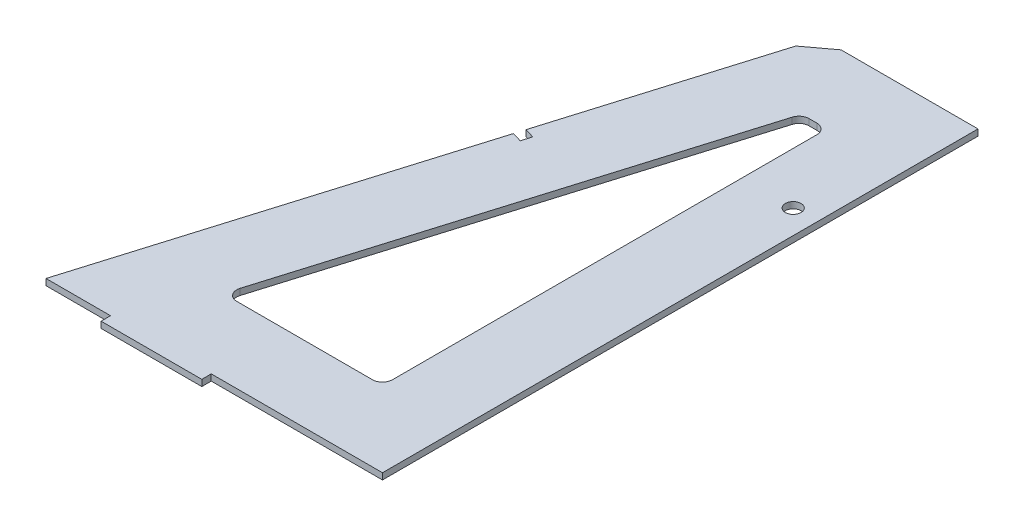
SolidWorks part; units mm, degrees
material "Balsa"
ref_plane "Front Plane" through (0, 0, 0) normal (0, 0, 1) x (1, 0, 0)
ref_plane "Top Plane" through (0, 0, 0) normal (0, 1, 0) x (1, 0, 0)
ref_plane "Right Plane" through (0, 0, 0) normal (1, 0, 0) x (0, 0, -1)
sketch "Sketch2" plane through (0, 0, 0) normal (0, 1, 0) x (1, 0, 0)
  line L0 (0, 0) -> (0, -214.2319) construction
  line L1 (0, 0) -> (202.3588, 0) construction
  line L2 (0, 0) -> (-115.8892, 0)
  line L3 (-115.8892, 0) -> (-25.4, 300.355)
  line L4 (-25.4, 300.355) -> (0, 300.355)
  line L5 (0, 300.355) -> (0, 0)
  dimension "D1" = 300.355
  dimension "D2" = 25.4
  dimension "D3" = 313.69
extrude "Boss-Extrude1" add sketch "Sketch2" along normal blind 3.175
sketch "Sketch4" plane through (0, 0, 0) normal (0, 0, 1) x (1, 0, 0)
  line L0 (-57.9446, 3.175) -> (-57.9446, 0) construction
  line L1 (-115.8892, 3.175) -> (0, 3.175) construction
  line L2 (-115.8892, 0) -> (0, 0) construction
  line L4 (-83.3446, 3.175) -> (-32.5446, 3.175)
  line L5 (-83.3446, 3.175) -> (-83.3446, 0)
  line L6 (-83.3446, 0) -> (-32.5446, 0)
  line L7 (-32.5446, 3.175) -> (-32.5446, 0)
  line L8 (-83.3446, 3.175) -> (-32.5446, 0) construction
  line L9 (-83.3446, 0) -> (-32.5446, 3.175) construction
  point P6 (-57.9446, 1.5875)
  dimension "D1" = 50.8
extrude "Boss-Extrude2" add sketch "Sketch4" along normal blind 4.7625
sketch "Sketch6" plane through (0, 0, 0) normal (1, 0, 0) x (0, 0, -1)
  line L4 (0, 0) -> (300.355, 0)
  line L5 (300.355, 0) -> (300.355, 3.175)
  line L6 (300.355, 3.175) -> (0, 3.175)
  line L7 (0, 3.175) -> (0, 0)
  line L8 (0, 0) -> (300.355, 0)
  line L9 (300.355, 0) -> (300.355, 3.175)
  line L10 (300.355, 3.175) -> (0, 3.175)
  line L11 (0, 3.175) -> (0, 0)
  dimension "D1" = 0
extrude "Boss-Extrude3" add sketch "Sketch6" along normal blind 53.819
sketch "Sketch7" plane through (0, 3.175, 0) normal (0, 1, 0) x (1, 0, 0)
  line L0 (41.754, 0) -> (41.754, 300.355) construction
  line L1 (-32.5446, 0) -> (53.819, 0) construction
  line L2 (53.819, 300.355) -> (-25.4, 300.355) construction
  line L3 (53.819, 300.355) -> (53.819, 0) construction
  line L4 (-28.3308, 290.6269) -> (-15.24, 300.355)
  line L5 (-25.4, 300.355) -> (-115.8892, 0) construction
  line L6 (-15.24, 300.355) -> (-25.4, 300.355)
  line L7 (-25.4, 300.355) -> (-28.3308, 290.6269)
  circle A0 centre (41.754, 219.202) radius 3.9687
  dimension "D2" = 7.9375
  dimension "D1" = 12.065
  dimension "D3" = 219.202
  dimension "D4" = 10.16
  dimension "D5" = 10.16
extrude "Cut-Extrude3" cut sketch "Sketch7" against normal through all
sketch "Sketch8" plane through (0, 3.175, 0) normal (0, 1, 0) x (1, 0, 0)
  line L9 (-64.6191, 38.1) -> (15.719, 38.1)
  line L10 (-64.6191, 38.1) -> (15.719, 38.1)
  line L17 (15.719, 38.1) -> (15.719, 262.255)
  line L18 (15.719, 262.255) -> (2.913, 262.255)
  line L19 (2.913, 262.255) -> (-64.6191, 38.1)
  line L21 (15.719, 38.1) -> (15.719, 262.255)
  line L22 (15.719, 262.255) -> (2.913, 262.255)
  line L23 (2.913, 262.255) -> (-64.6191, 38.1)
  dimension "D1" = 38.1
extrude "Cut-Extrude4" cut sketch "Sketch8" against normal through all
fillet "Fillet1" radius 5.08 4 edges at (2.913, 1.5875, -262.255) (15.719, 1.5875, -262.255) (15.719, 1.5875, -38.1) (-64.6191, 1.5875, -38.1)
sketch "Sketch9" plane through (0, 3.175, 0) normal (0, 1, 0) x (1, 0, 0)
  line L0 (-115.8892, 0) -> (-59.8372, 186.0499) construction
  line L1 (-28.3308, 290.6269) -> (-115.8892, 0) construction
  line L2 (-59.8372, 186.0499) -> (-54.9731, 184.5844)
  line L3 (-54.9731, 184.5844) -> (-56.4385, 179.7204)
  line L4 (-56.4385, 179.7204) -> (-61.3026, 181.1858)
  line L5 (-61.3026, 181.1858) -> (-59.8372, 186.0499)
  dimension "D1" = 194.31
  dimension "D2" = 5.08
  dimension "D3" = 5.08
extrude "Cut-Extrude5" cut sketch "Sketch9" against normal through all
